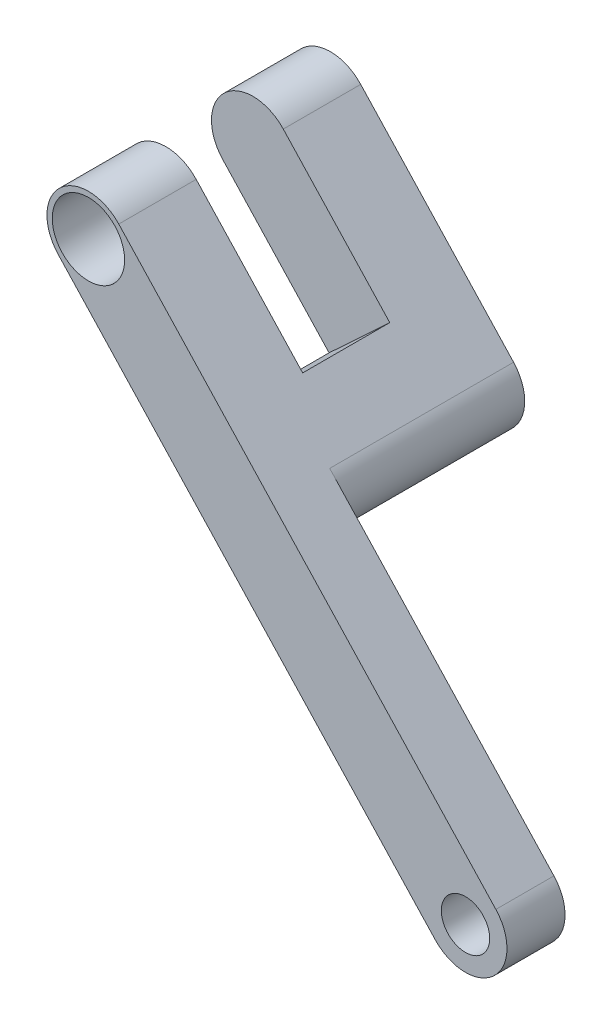
SolidWorks part; units mm, degrees
ref_plane "Front Plane" through (0, 0, 0) normal (0, 0, 1) x (1, 0, 0)
ref_plane "Top Plane" through (0, 0, 0) normal (0, 1, 0) x (1, 0, 0)
ref_plane "Right Plane" through (0, 0, 0) normal (1, 0, 0) x (0, 0, -1)
sketch "Sketch1" plane through (0, 0, 0) normal (0, 0, 1) x (1, 0, 0)
  line L0 (19.835, -29.1815) -> (27.7336, -37.6651) construction
  line L1 (21.403, -27.7217) -> (29.3016, -36.2052)
  line L2 (18.267, -30.6414) -> (26.1656, -39.125)
  line L3 (19.835, -29.1815) -> (89.335, -103.8283) construction
  circle A1 centre (19.835, -29.1815) radius 1.8694
  arc A2 (21.403, -27.7217) -> (18.267, -30.6414) centre (19.835, -29.1815) ccw
  arc A3 (26.1656, -39.125) -> (29.3016, -36.2052) centre (27.7336, -37.6651) ccw
  point P3 (23.7843, -33.4233)
extrude "Boss-Extrude1" add sketch "Sketch1" along normal blind 4
sketch "Sketch2" plane through (0, 0, 0) normal (0, 0, -1) x (-1, 0, 0)
  line L0 (-29.3016, -36.2052) -> (-21.403, -27.7217) construction
  line L1 (-18.267, -30.6414) -> (-26.1656, -39.125) construction
  line L2 (-29.3016, -36.2052) -> (-26.9048, -33.6309)
  line L3 (-23.7688, -36.5507) -> (-26.1656, -39.125)
  line L4 (-23.7688, -36.5507) -> (-26.9048, -33.6309)
  arc A0 (-29.3016, -36.2052) -> (-26.1656, -39.125) centre (-27.7336, -37.6651) ccw construction
  arc A1 (-29.3016, -36.2052) -> (-26.1656, -39.125) centre (-27.7336, -37.6651) ccw
extrude "Boss-Extrude2" add sketch "Sketch2" along normal blind 4.5
sketch "Sketch3" plane through (0, 0, -4.5) normal (0, 0, -1) x (-1, 0, 0)
  line L0 (-26.1656, -39.125) -> (-23.7688, -36.5507) construction
  line L2 (-26.9048, -33.6309) -> (-29.3016, -36.2052) construction
  line L4 (-23.7688, -36.5507) -> (-18.267, -30.6414) construction
  line L5 (-21.403, -27.7217) -> (-26.9048, -33.6309) construction
  line L6 (-26.1656, -39.125) -> (-23.7688, -36.5507)
  line L8 (-26.9048, -33.6309) -> (-29.3016, -36.2052)
  line L10 (-23.7688, -36.5507) -> (-18.267, -30.6414)
  line L11 (-21.403, -27.7217) -> (-26.9048, -33.6309)
  arc A0 (-29.3016, -36.2052) -> (-26.1656, -39.125) centre (-27.7336, -37.6651) ccw construction
  arc A1 (-18.267, -30.6414) -> (-21.403, -27.7217) centre (-19.835, -29.1815) ccw construction
  arc A2 (-29.3016, -36.2052) -> (-26.1656, -39.125) centre (-27.7336, -37.6651) ccw
  arc A3 (-18.267, -30.6414) -> (-21.403, -27.7217) centre (-19.835, -29.1815) ccw
extrude "Boss-Extrude3" add sketch "Sketch3" along normal blind 4
sketch "Sketch6" plane through (0, 0, 4) normal (0, 0, 1) x (1, 0, 0)
  line L0 (29.3016, -36.2052) -> (21.403, -27.7217) construction
  line L1 (18.267, -30.6414) -> (26.1656, -39.125) construction
  line L2 (39.3178, -50.1072) -> (27.7336, -37.6651) construction
  line L3 (37.7498, -51.5671) -> (26.1656, -39.125)
  line L4 (40.8858, -48.6473) -> (29.3016, -36.2052)
  circle A1 centre (39.3178, -50.1072) radius 1.25
  arc A5 (37.7498, -51.5671) -> (40.8858, -48.6473) centre (39.3178, -50.1072) ccw
  arc A6 (29.3016, -36.2052) -> (26.1656, -39.125) centre (27.7336, -37.6651) ccw
  point P9 (33.5257, -43.8861)
  dimension "D1" = 17
extrude "Boss-Extrude4" add sketch "Sketch6" against normal blind 3
sketch "Sketch7" plane through (0, 0, 4) normal (0, 0, 1) x (1, 0, 0)
  point P5 (97.1119, -112.1812)
ref_point "Point1"
